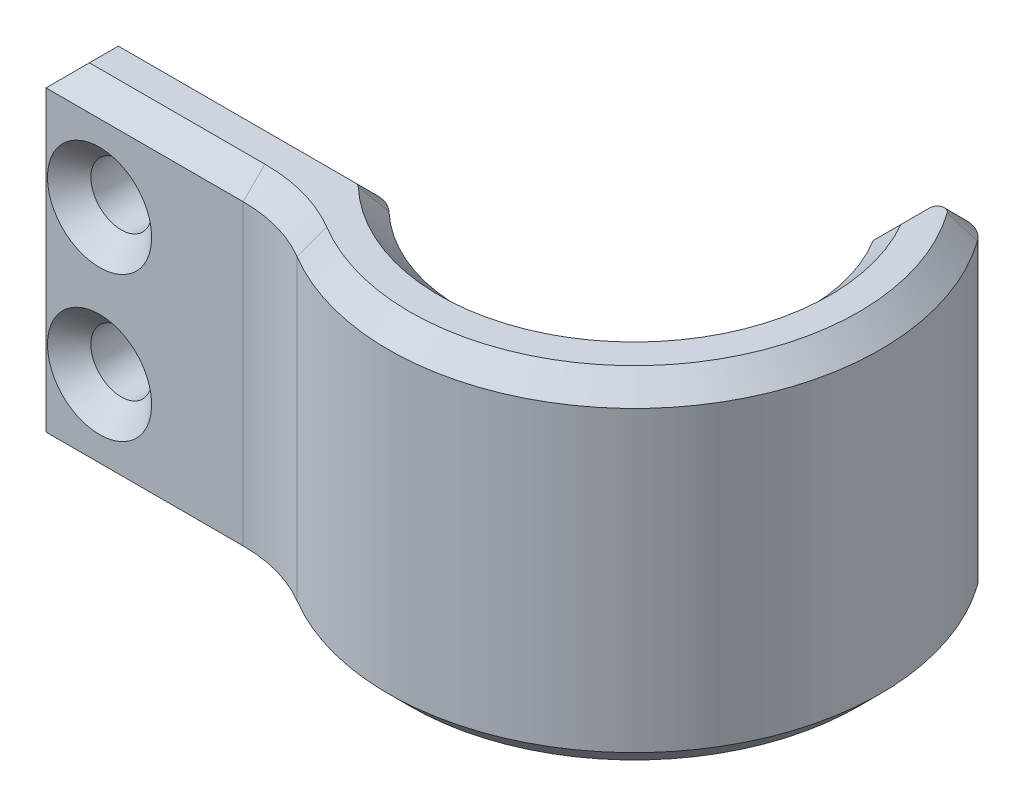
SolidWorks part; units mm, degrees
ref_plane "Alzado" through (0, 0, 0) normal (0, 0, 1) x (1, 0, 0)
ref_plane "Planta" through (0, 0, 0) normal (0, 1, 0) x (1, 0, 0)
ref_plane "Vista lateral" through (0, 0, 0) normal (1, 0, 0) x (0, 0, -1)
sketch "Croquis1" plane through (0, 0, 0) normal (0, 0, 1) x (1, 0, 0)
  line L0 (0, -11.8) -> (34.55, -11.8) construction
  line L1 (20.55, -11.8) -> (36.05, -11.8)
  line L2 (20.55, -11.8) -> (20.55, 11.8)
  line L3 (20.55, 11.8) -> (36.05, 11.8)
  line L4 (36.05, -11.8) -> (36.05, 11.8)
  line L5 (20.45, -10.3) -> (20.45, 10.3) construction
  line L6 (36.05, 13.3) -> (36.05, -13.3) construction
  line L7 (34.55, 11.8) -> (0, 11.8) construction
  circle A0 centre (24.25, -5) radius 2.1
  circle A1 centre (24.25, 5) radius 2.1
  circle A2 centre (24.25, -5) radius 2.1 construction
  dimension "D1" = 0.1
extrude "Saliente-Extruir1" add sketch "Croquis1" along normal blind 5
sketch "Croquis2" plane through (0, 0, 0) normal (0, 1, 0) x (1, 0, 0)
  line L0 (36.05, 12.9255) -> (36.05, 3.4021)
  line L1 (36.05, 1.5) -> (36.05, 47.6) construction
  line L2 (36.05, -5) -> (37.2929, -5)
  line L3 (36.05, 0) -> (39.255, 0)
  line L4 (58.2685, 21.7499) -> (58.2685, 14.4552)
  line L5 (36.05, 0) -> (36.05, -5)
  circle A0 centre (48.05, 8.1638) radius 12 construction
  arc A1 (37.2929, -5) -> (58.2685, 21.7499) centre (48.05, 8.1638) ccw
  arc A2 (39.255, 0) -> (58.2685, 14.4552) centre (48.05, 8.1638) ccw
  point P6 (36.05, 8.1638)
  dimension "D1" = 24
  dimension "D3" = 5
  dimension "D2" = 0
extrude "Saliente-Extruir2" add sketch "Croquis2" against normal up to surface and the other way up to surface contours A2 L3 L5 L2 A1 L4 up to face at (28.3, -11.8, 2.5) other way up to face at (28.3, 11.8, 2.5)
fillet "Redondeo1" radius 2 2 edges at (39.255, 0, 0) (58.2685, 0, -21.7499)
fillet "Redondeo2" radius 10 1 edges at (37.2929, 0, 5)
chamfer "Chaflán1" distance 1.5 angle 45 18 edges at (58.2685, 11.8, -15.66) (58.2685, -11.8, -15.66) (59.6595, 11.8, -18.7699) (60.5374, 11.8, 3.3716) (60.5374, -11.8, 3.3716) (36.8431, 11.8, 5.3617) (27.3639, 11.8, 5) (20.55, 11.8, 2.5) (29.486, 11.8, 0) (39.1623, 11.8, 0.1421) (55.6158, -11.8, 1.1507) (55.6158, 11.8, 1.1507) (20.55, -11.8, 2.5) (27.3639, -11.8, 5) (36.8431, -11.8, 5.3617) (59.6595, -11.8, -18.7699) (39.1623, -11.8, 0.1421) (29.486, -11.8, 0)
chamfer "Chaflán2" distance 1.5 angle 45 2 edges at (26.35, 5, 5) (26.35, -5, 5)
sketch "Croquis3" plane through (0, 0, 0) normal (0, 0, -1) x (-1, 0, 0)
  line L3 (-36.1099, -10.7525) -> (-36.1099, 10.3)
  line L4 (-20.55, 10.3) -> (-38.422, 10.3) construction
